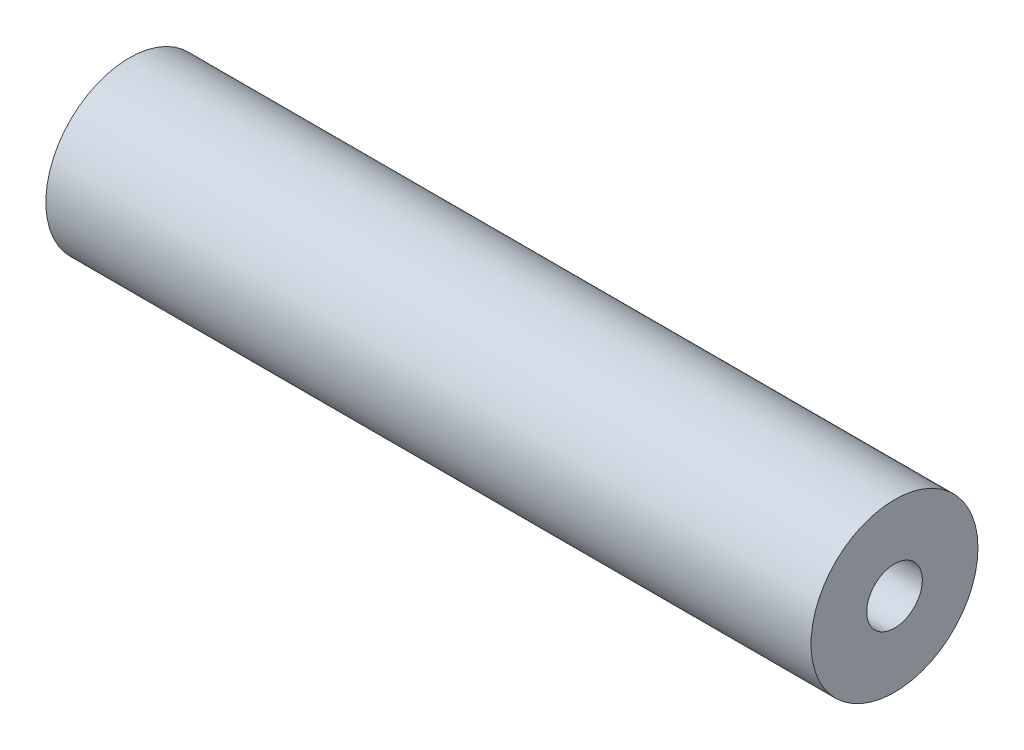
SolidWorks part; units mm, degrees
ref_plane "Front Plane" through (0, 0, 0) normal (0, 0, 1) x (1, 0, 0)
ref_plane "Top Plane" through (0, 0, 0) normal (0, 1, 0) x (1, 0, 0)
ref_plane "Right Plane" through (0, 0, 0) normal (1, 0, 0) x (0, 0, -1)
sketch "Sketch1" plane through (0, 0, 0) normal (1, 0, 0) x (0, 0, -1)
  circle A0 centre (0, 0) radius 12
  dimension "D1" = 24
extrude "Boss-Extrude1" add sketch "Sketch1" along normal blind 110
sketch "Sketch2" plane through (110, 0, 0) normal (1, 0, 0) x (0, 0, -1)
  circle A0 centre (0, 0) radius 4
  dimension "D1" = 8
extrude "Cut-Extrude1" cut sketch "Sketch2" against normal blind 222
